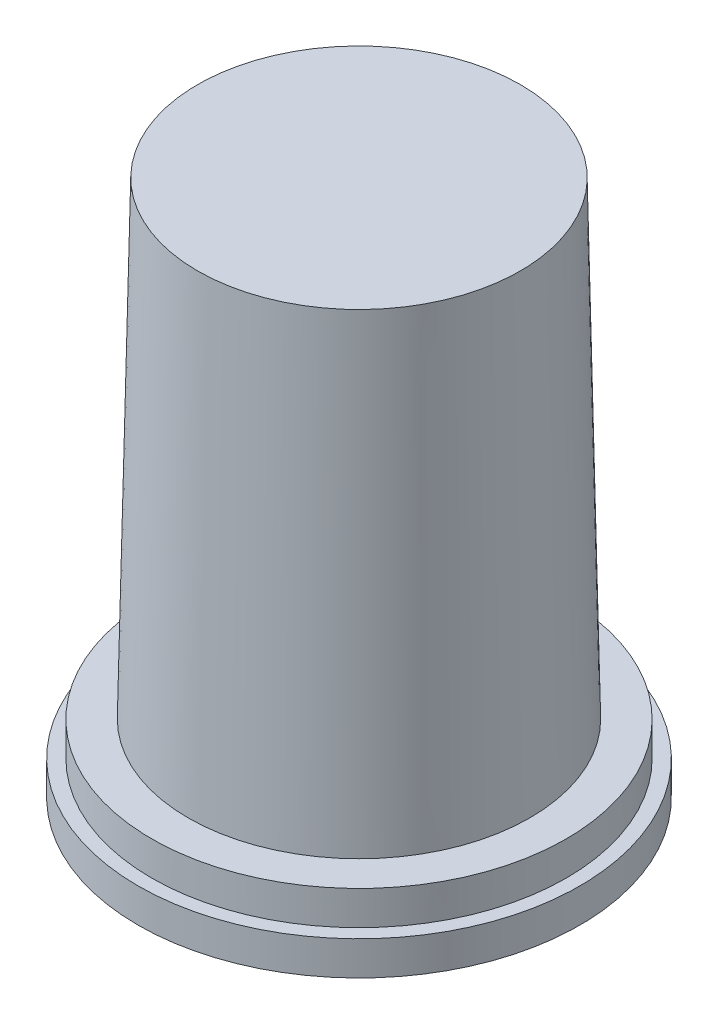
SolidWorks part; units mm, degrees
material "Tin Bearing Bronze"
ref_plane "Front Plane" through (0, 0, 0) normal (0, 0, 1) x (1, 0, 0)
ref_plane "Top Plane" through (0, 0, 0) normal (0, 1, 0) x (1, 0, 0)
ref_plane "Right Plane" through (0, 0, 0) normal (1, 0, 0) x (0, 0, -1)
sketch "MainBodyS" plane through (0, 0, 0) normal (0, 0, 1) x (1, 0, 0)
  line L0 (0, 15.8) -> (4.75, 15.8)
  line L1 (4.75, 15.8) -> (5.05, 1)
  line L2 (5.05, 1) -> (6.5, 1)
  line L3 (6.5, 1) -> (6.5, 0)
  line L4 (6.5, 0) -> (4.0701, 0)
  line L5 (4.0701, 0) -> (3.7843, 14.1)
  line L6 (3.7843, 14.1) -> (0, 14.1)
  line L7 (0, 14.1) -> (0, 15.8)
  line L8 (0, 0) -> (0, 14.1) construction
  dimension "D1" = 1
  dimension "TopDia" = 9.5
  dimension "D2" = 13
  dimension "WallThickness" = 1.7
  dimension "D3" = 14.8
  dimension "D4" = 1
  dimension "BottomDiaControl" = 0.3
revolve "MainBody" add sketch "MainBodyS" angle 360 about L8
sketch "InsertBodyS" plane through (0, 0, 0) normal (0, 0, 1) x (1, 0, 0)
  line L0 (5.0297, 2) -> (6.1, 2)
  line L1 (5.05, 1) -> (4.75, 15.8) construction
  line L2 (6.1, 2) -> (6.1, 1)
  line L3 (6.1, 1) -> (5.05, 1)
  line L4 (5.05, 1) -> (5.0297, 2)
  line L5 (6.5, 1) -> (-6.5, 1) construction
  dimension "DiaControl" = 1.05
  dimension "Height" = 1
revolve "InsertBody" add sketch "InsertBodyS" angle 360 about axis through (0, 1, 0) along (0, -1, 0)
fillet "InsideBoreF" radius 0.5 1 edges at (0, 0, -4.0701)
